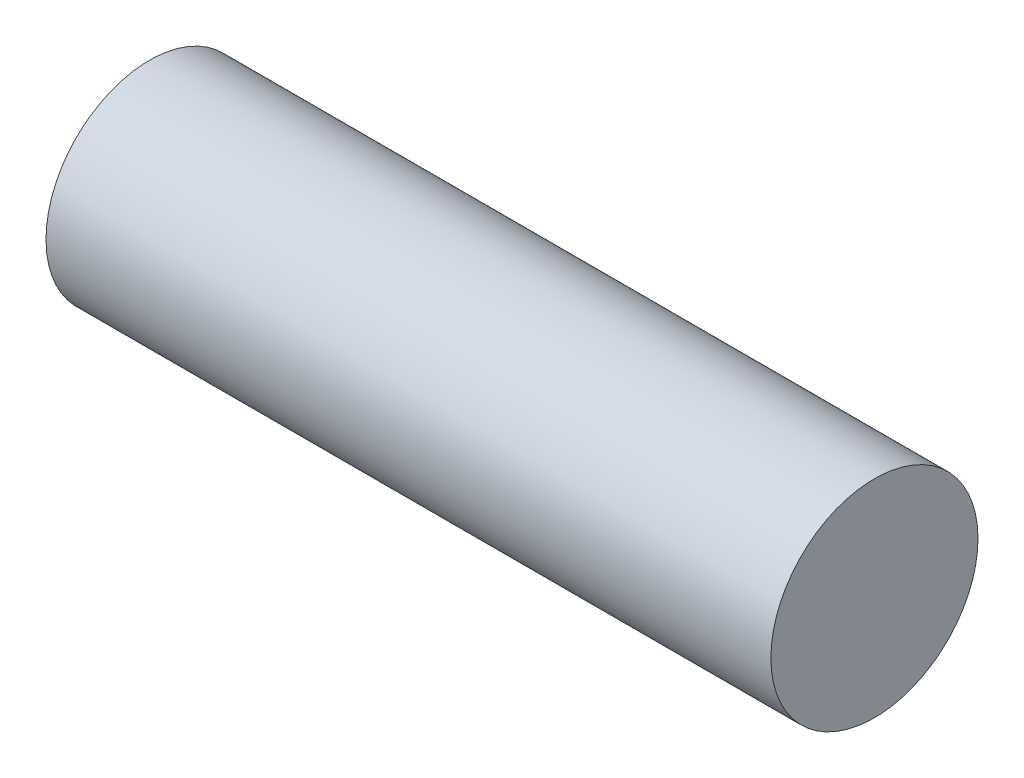
SolidWorks part; units mm, degrees
ref_plane "Front Plane" through (0, 0, 0) normal (0, 0, 1) x (1, 0, 0)
ref_plane "Top Plane" through (0, 0, 0) normal (0, 1, 0) x (1, 0, 0)
ref_plane "Right Plane" through (0, 0, 0) normal (1, 0, 0) x (0, 0, -1)
sketch "Sketch1" plane through (0, 0, 0) normal (1, 0, 0) x (0, 0, -1)
  circle A0 centre (0, 0) radius 1
  dimension "D1" = 2
extrude "Boss-Extrude1" add sketch "Sketch1" along normal blind 7
